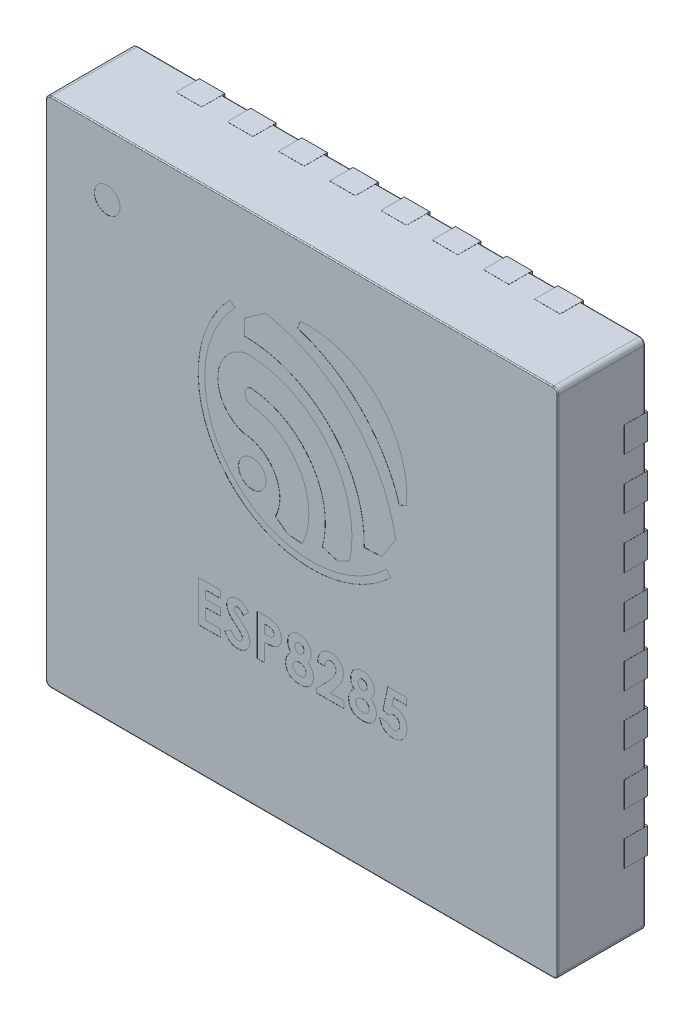
SolidWorks part; units mm, degrees
other "ESP8285-SoC" parameters "D5"=0.3678, "D1"=3.1308, "D2"=3.0402, "D3"=0.4115, "D4"=0.3, "D6"=0.3296, "D7"=0.2637, "D8"=0.9806, "D10"=0.5, "D11"=0.25, "D9"=4
ref_plane "Front Plane" through (0, 0, 0) normal (0, 0, 1) x (1, 0, 0)
ref_plane "Top Plane" through (0, 0, 0) normal (0, 1, 0) x (1, 0, 0)
ref_plane "Right Plane" through (0, 0, 0) normal (1, 0, 0) x (0, 0, -1)
sketch "Sketch1" plane through (0, 0, 0) normal (0, 1, 0) x (1, 0, 0)
  line L1 (-2.5, -2.5) -> (2.5, -2.5)
  line L2 (-2.5, -2.5) -> (-2.5, 2.5)
  line L3 (-2.5, 2.5) -> (2.5, 2.5)
  line L4 (2.5, -2.5) -> (2.5, 2.5)
  line L5 (-2.5, -2.5) -> (2.5, 2.5) construction
  line L6 (-2.5, 2.5) -> (2.5, -2.5) construction
  point P0 (0, 0)
  dimension "D1" = 5
  dimension "D2" = 5
extrude "Boss-Extrude1" add sketch "Sketch1" along normal blind 0.85
fillet "Fillet1" radius 0.05 4 edges at (2.5, 0.425, -2.5) (2.5, 0.425, 2.5) (-2.5, 0.425, 2.5) (-2.5, 0.425, -2.5)
fillet "Fillet2" radius 0.01 16 edges at (2.4854, 0.85, 2.4854) (0, 0.85, 2.5) (-2.4854, 0.85, 2.4854) (-2.5, 0.85, 0) (-2.4854, 0.85, -2.4854) (0, 0.85, -2.5) (2.4854, 0.85, -2.4854) (2.5, 0.85, 0) (2.5, 0, 0) (2.4854, 0, -2.4854) (0, 0, -2.5) (2.4854, 0, 2.4854) (0, 0, 2.5) (-2.4854, 0, 2.4854) (-2.5, 0, 0) (-2.4854, 0, -2.4854)
sketch "Sketch2" plane through (0, 0, 0) normal (0, -1, 0) x (1, 0, 0)
  line L0 (1.55, 1.85) -> (1.85, 1.55)
  line L1 (-1.8, -1.85) -> (1.8, -1.85)
  line L2 (-1.85, -1.8) -> (-1.85, 1.8)
  line L3 (-1.8, 1.85) -> (1.55, 1.85)
  line L4 (1.85, -1.8) -> (1.85, 1.55)
  line L5 (-1.8354, -1.8354) -> (1.85, 1.85) construction
  line L6 (-1.8354, 1.8354) -> (1.8354, -1.8354) construction
  line L7 (1.55, 1.85) -> (1.85, 1.85) construction
  line L8 (1.85, 1.55) -> (1.85, 1.85) construction
  line L9 (-1.85, 1.85) -> (-1.8, 1.85) construction
  line L10 (-1.85, 1.85) -> (-1.8354, 1.8354) construction
  line L11 (-1.85, 1.8) -> (-1.85, 1.85) construction
  line L12 (-1.85, -1.85) -> (-1.85, -1.8) construction
  line L13 (-1.85, -1.85) -> (-1.8354, -1.8354) construction
  line L14 (-1.85, -1.85) -> (-1.8, -1.85) construction
  line L15 (1.85, -1.85) -> (1.85, -1.8) construction
  line L16 (1.8354, -1.8354) -> (1.85, -1.85) construction
  line L17 (1.8, -1.85) -> (1.85, -1.85) construction
  line L18 (0, -1000) -> (0, 49000) construction
  line L23 (-0.375, 2.501) -> (-0.125, 2.501)
  line L24 (-0.375, 2.501) -> (-0.375, 2.101)
  line L25 (-0.375, 2.101) -> (-0.125, 2.101)
  line L26 (-0.125, 2.501) -> (-0.125, 2.101)
  line L27 (-0.375, 2.501) -> (-0.125, 2.101) construction
  line L28 (-0.375, 2.101) -> (-0.125, 2.501) construction
  line L30 (-0.875, 2.501) -> (-0.875, 2.101)
  line L31 (-0.875, 2.501) -> (-0.625, 2.501)
  line L32 (-0.625, 2.501) -> (-0.625, 2.101)
  line L33 (-0.875, 2.101) -> (-0.625, 2.101)
  line L34 (-0.875, 2.101) -> (-0.625, 2.501) construction
  line L35 (-0.875, 2.501) -> (-0.625, 2.101) construction
  line L36 (-1.375, 2.501) -> (-1.375, 2.101)
  line L37 (-1.375, 2.501) -> (-1.125, 2.501)
  line L38 (-1.125, 2.501) -> (-1.125, 2.101)
  line L39 (-1.375, 2.101) -> (-1.125, 2.101)
  line L40 (-1.375, 2.101) -> (-1.125, 2.501) construction
  line L41 (-1.375, 2.501) -> (-1.125, 2.101) construction
  line L42 (-1.875, 2.501) -> (-1.875, 2.101)
  line L43 (-1.875, 2.501) -> (-1.625, 2.501)
  line L44 (-1.625, 2.501) -> (-1.625, 2.101)
  line L45 (-1.875, 2.101) -> (-1.625, 2.101)
  line L46 (-1.875, 2.101) -> (-1.625, 2.501) construction
  line L47 (-1.875, 2.501) -> (-1.625, 2.101) construction
  line L48 (-0.375, 2.501) -> (-0.875, 2.501) construction
  line L162 (-1000, 0) -> (49000, 0) construction
  line L163 (-2.5, 2.5) -> (2.5, 2.5) construction
  line L164 (0.375, 2.501) -> (0.875, 2.501) construction
  line L165 (1.875, 2.501) -> (1.625, 2.101) construction
  line L166 (1.875, 2.101) -> (1.625, 2.501) construction
  line L167 (1.375, 2.501) -> (1.125, 2.101) construction
  line L168 (1.375, 2.101) -> (1.125, 2.501) construction
  line L169 (0.875, 2.501) -> (0.625, 2.101) construction
  line L170 (0.875, 2.101) -> (0.625, 2.501) construction
  line L171 (0.375, 2.101) -> (0.125, 2.501) construction
  line L172 (0.375, 2.501) -> (0.125, 2.101) construction
  line L173 (1.875, 2.101) -> (1.625, 2.101)
  line L174 (1.625, 2.501) -> (1.625, 2.101)
  line L175 (1.875, 2.501) -> (1.625, 2.501)
  line L176 (1.875, 2.501) -> (1.875, 2.101)
  line L177 (1.375, 2.101) -> (1.125, 2.101)
  line L178 (1.125, 2.501) -> (1.125, 2.101)
  line L179 (1.375, 2.501) -> (1.125, 2.501)
  line L180 (1.375, 2.501) -> (1.375, 2.101)
  line L181 (0.875, 2.101) -> (0.625, 2.101)
  line L182 (0.625, 2.501) -> (0.625, 2.101)
  line L183 (0.875, 2.501) -> (0.625, 2.501)
  line L184 (0.875, 2.501) -> (0.875, 2.101)
  line L185 (0.125, 2.501) -> (0.125, 2.101)
  line L186 (0.375, 2.101) -> (0.125, 2.101)
  line L187 (0.375, 2.501) -> (0.375, 2.101)
  line L188 (0.375, 2.501) -> (0.125, 2.501)
  line L189 (0.375, -2.501) -> (0.125, -2.101) construction
  line L190 (0.375, -2.101) -> (0.125, -2.501) construction
  line L191 (0.875, -2.101) -> (0.625, -2.501) construction
  line L192 (0.875, -2.501) -> (0.625, -2.101) construction
  line L193 (1.375, -2.101) -> (1.125, -2.501) construction
  line L194 (1.375, -2.501) -> (1.125, -2.101) construction
  line L195 (1.875, -2.101) -> (1.625, -2.501) construction
  line L196 (1.875, -2.501) -> (1.625, -2.101) construction
  line L197 (0.375, -2.501) -> (0.875, -2.501) construction
  line L198 (-0.375, -2.501) -> (-0.875, -2.501) construction
  line L199 (-1.875, -2.501) -> (-1.625, -2.101) construction
  line L200 (-1.875, -2.101) -> (-1.625, -2.501) construction
  line L201 (-1.375, -2.501) -> (-1.125, -2.101) construction
  line L202 (-1.375, -2.101) -> (-1.125, -2.501) construction
  line L203 (-0.875, -2.501) -> (-0.625, -2.101) construction
  line L204 (-0.875, -2.101) -> (-0.625, -2.501) construction
  line L205 (-0.375, -2.101) -> (-0.125, -2.501) construction
  line L206 (-0.375, -2.501) -> (-0.125, -2.101) construction
  line L207 (0.375, -2.501) -> (0.125, -2.501)
  line L208 (0.375, -2.501) -> (0.375, -2.101)
  line L209 (0.375, -2.101) -> (0.125, -2.101)
  line L210 (0.125, -2.501) -> (0.125, -2.101)
  line L211 (0.875, -2.501) -> (0.875, -2.101)
  line L212 (0.875, -2.501) -> (0.625, -2.501)
  line L213 (0.625, -2.501) -> (0.625, -2.101)
  line L214 (0.875, -2.101) -> (0.625, -2.101)
  line L215 (1.375, -2.501) -> (1.375, -2.101)
  line L216 (1.375, -2.501) -> (1.125, -2.501)
  line L217 (1.125, -2.501) -> (1.125, -2.101)
  line L218 (1.375, -2.101) -> (1.125, -2.101)
  line L219 (1.875, -2.501) -> (1.875, -2.101)
  line L220 (1.875, -2.501) -> (1.625, -2.501)
  line L221 (1.625, -2.501) -> (1.625, -2.101)
  line L222 (1.875, -2.101) -> (1.625, -2.101)
  line L223 (-1.875, -2.101) -> (-1.625, -2.101)
  line L224 (-1.625, -2.501) -> (-1.625, -2.101)
  line L225 (-1.875, -2.501) -> (-1.625, -2.501)
  line L226 (-1.875, -2.501) -> (-1.875, -2.101)
  line L227 (-1.375, -2.101) -> (-1.125, -2.101)
  line L228 (-1.125, -2.501) -> (-1.125, -2.101)
  line L229 (-1.375, -2.501) -> (-1.125, -2.501)
  line L230 (-1.375, -2.501) -> (-1.375, -2.101)
  line L231 (-0.875, -2.101) -> (-0.625, -2.101)
  line L232 (-0.625, -2.501) -> (-0.625, -2.101)
  line L233 (-0.875, -2.501) -> (-0.625, -2.501)
  line L234 (-0.875, -2.501) -> (-0.875, -2.101)
  line L235 (-0.125, -2.501) -> (-0.125, -2.101)
  line L236 (-0.375, -2.101) -> (-0.125, -2.101)
  line L237 (-0.375, -2.501) -> (-0.375, -2.101)
  line L238 (-0.375, -2.501) -> (-0.125, -2.501)
  line L239 (2.501, 0.375) -> (2.101, 0.125) construction
  line L240 (2.101, 0.375) -> (2.501, 0.125) construction
  line L241 (2.101, 0.875) -> (2.501, 0.625) construction
  line L242 (2.501, 0.875) -> (2.101, 0.625) construction
  line L243 (2.101, 1.375) -> (2.501, 1.125) construction
  line L244 (2.501, 1.375) -> (2.101, 1.125) construction
  line L245 (2.101, 1.875) -> (2.501, 1.625) construction
  line L246 (2.501, 1.875) -> (2.101, 1.625) construction
  line L247 (2.501, 0.375) -> (2.501, 0.875) construction
  line L248 (2.501, -0.375) -> (2.501, -0.875) construction
  line L249 (2.501, -1.875) -> (2.101, -1.625) construction
  line L250 (2.101, -1.875) -> (2.501, -1.625) construction
  line L251 (2.501, -1.375) -> (2.101, -1.125) construction
  line L252 (2.101, -1.375) -> (2.501, -1.125) construction
  line L253 (2.501, -0.875) -> (2.101, -0.625) construction
  line L254 (2.101, -0.875) -> (2.501, -0.625) construction
  line L255 (2.101, -0.375) -> (2.501, -0.125) construction
  line L256 (2.501, -0.375) -> (2.101, -0.125) construction
  line L257 (2.501, 0.375) -> (2.501, 0.125)
  line L258 (2.501, 0.375) -> (2.101, 0.375)
  line L259 (2.101, 0.375) -> (2.101, 0.125)
  line L260 (2.501, 0.125) -> (2.101, 0.125)
  line L261 (2.501, 0.875) -> (2.101, 0.875)
  line L262 (2.501, 0.875) -> (2.501, 0.625)
  line L263 (2.501, 0.625) -> (2.101, 0.625)
  line L264 (2.101, 0.875) -> (2.101, 0.625)
  line L265 (2.501, 1.375) -> (2.101, 1.375)
  line L266 (2.501, 1.375) -> (2.501, 1.125)
  line L267 (2.501, 1.125) -> (2.101, 1.125)
  line L268 (2.101, 1.375) -> (2.101, 1.125)
  line L269 (2.501, 1.875) -> (2.101, 1.875)
  line L270 (2.501, 1.875) -> (2.501, 1.625)
  line L271 (2.501, 1.625) -> (2.101, 1.625)
  line L272 (2.101, 1.875) -> (2.101, 1.625)
  line L273 (2.101, -1.875) -> (2.101, -1.625)
  line L274 (2.501, -1.625) -> (2.101, -1.625)
  line L275 (2.501, -1.875) -> (2.501, -1.625)
  line L276 (2.501, -1.875) -> (2.101, -1.875)
  line L277 (2.101, -1.375) -> (2.101, -1.125)
  line L278 (2.501, -1.125) -> (2.101, -1.125)
  line L279 (2.501, -1.375) -> (2.501, -1.125)
  line L280 (2.501, -1.375) -> (2.101, -1.375)
  line L281 (2.101, -0.875) -> (2.101, -0.625)
  line L282 (2.501, -0.625) -> (2.101, -0.625)
  line L283 (2.501, -0.875) -> (2.501, -0.625)
  line L284 (2.501, -0.875) -> (2.101, -0.875)
  line L285 (2.501, -0.125) -> (2.101, -0.125)
  line L286 (2.101, -0.375) -> (2.101, -0.125)
  line L287 (2.501, -0.375) -> (2.101, -0.375)
  line L288 (2.501, -0.375) -> (2.501, -0.125)
  line L289 (-2.501, -0.375) -> (-2.101, -0.125) construction
  line L290 (-2.101, -0.375) -> (-2.501, -0.125) construction
  line L291 (-2.101, -0.875) -> (-2.501, -0.625) construction
  line L292 (-2.501, -0.875) -> (-2.101, -0.625) construction
  line L293 (-2.101, -1.375) -> (-2.501, -1.125) construction
  line L294 (-2.501, -1.375) -> (-2.101, -1.125) construction
  line L295 (-2.101, -1.875) -> (-2.501, -1.625) construction
  line L296 (-2.501, -1.875) -> (-2.101, -1.625) construction
  line L297 (-2.501, -0.375) -> (-2.501, -0.875) construction
  line L298 (-2.501, 0.375) -> (-2.501, 0.875) construction
  line L299 (-2.501, 1.875) -> (-2.101, 1.625) construction
  line L300 (-2.101, 1.875) -> (-2.501, 1.625) construction
  line L301 (-2.501, 1.375) -> (-2.101, 1.125) construction
  line L302 (-2.101, 1.375) -> (-2.501, 1.125) construction
  line L303 (-2.501, 0.875) -> (-2.101, 0.625) construction
  line L304 (-2.101, 0.875) -> (-2.501, 0.625) construction
  line L305 (-2.101, 0.375) -> (-2.501, 0.125) construction
  line L306 (-2.501, 0.375) -> (-2.101, 0.125) construction
  line L307 (-2.501, -0.375) -> (-2.501, -0.125)
  line L308 (-2.501, -0.375) -> (-2.101, -0.375)
  line L309 (-2.101, -0.375) -> (-2.101, -0.125)
  line L310 (-2.501, -0.125) -> (-2.101, -0.125)
  line L311 (-2.501, -0.875) -> (-2.101, -0.875)
  line L312 (-2.501, -0.875) -> (-2.501, -0.625)
  line L313 (-2.501, -0.625) -> (-2.101, -0.625)
  line L314 (-2.101, -0.875) -> (-2.101, -0.625)
  line L315 (-2.501, -1.375) -> (-2.101, -1.375)
  line L316 (-2.501, -1.375) -> (-2.501, -1.125)
  line L317 (-2.501, -1.125) -> (-2.101, -1.125)
  line L318 (-2.101, -1.375) -> (-2.101, -1.125)
  line L319 (-2.501, -1.875) -> (-2.101, -1.875)
  line L320 (-2.501, -1.875) -> (-2.501, -1.625)
  line L321 (-2.501, -1.625) -> (-2.101, -1.625)
  line L322 (-2.101, -1.875) -> (-2.101, -1.625)
  line L323 (-2.101, 1.875) -> (-2.101, 1.625)
  line L324 (-2.501, 1.625) -> (-2.101, 1.625)
  line L325 (-2.501, 1.875) -> (-2.501, 1.625)
  line L326 (-2.501, 1.875) -> (-2.101, 1.875)
  line L327 (-2.101, 1.375) -> (-2.101, 1.125)
  line L328 (-2.501, 1.125) -> (-2.101, 1.125)
  line L329 (-2.501, 1.375) -> (-2.501, 1.125)
  line L330 (-2.501, 1.375) -> (-2.101, 1.375)
  line L331 (-2.101, 0.875) -> (-2.101, 0.625)
  line L332 (-2.501, 0.625) -> (-2.101, 0.625)
  line L333 (-2.501, 0.875) -> (-2.501, 0.625)
  line L334 (-2.501, 0.875) -> (-2.101, 0.875)
  line L335 (-2.501, 0.125) -> (-2.101, 0.125)
  line L336 (-2.101, 0.375) -> (-2.101, 0.125)
  line L337 (-2.501, 0.375) -> (-2.101, 0.375)
  line L338 (-2.501, 0.375) -> (-2.501, 0.125)
  arc A0 (-1.8, 1.85) -> (-1.85, 1.8) centre (-1.8, 1.8) ccw
  arc A1 (-1.85, -1.8) -> (-1.8, -1.85) centre (-1.8, -1.8) ccw
  arc A2 (1.8, -1.85) -> (1.85, -1.8) centre (1.8, -1.8) ccw
  point P0 (0, 0)
  point P12 (-0.25, 2.301)
  point P60 (0.25, 2.301)
  point P93 (0.25, -2.301)
  point P94 (-0.25, -2.301)
  point P127 (2.301, 0.25)
  point P128 (2.301, -0.25)
  point P161 (-2.301, -0.25)
  point P162 (-2.301, 0.25)
  dimension "D5" = 0.1
  dimension "D1" = 3.7
  dimension "D2" = 3.7
  dimension "D4" = 45
  dimension "D6" = 0.4
  dimension "D7" = 0.25
  dimension "D8" = 0.25
  dimension "D11" = 0.001
  dimension "D3" = 0.3
extrude "Boss-Extrude2" add sketch "Sketch2" along normal blind 0.025 and the other way blind 0.203
sketch "Sketch3" plane through (0, 0.85, 0) normal (0, 1, 0) x (1, 0, 0)
  line L7 (-2.5, 1.245) -> (2.5, 1.245) construction
  line L8 (-2.5, 2.5) -> (-2.5, -2.5) construction
  line L9 (2.45, -2.5) -> (-2.45, -2.5) construction
  line L11 (2.5, 2.45) -> (2.5, -2.45) construction
  line L12 (-0.9518, -0.7471) -> (-1.0208, -0.7765)
  line L13 (0.0158, -1.8185) -> (0.0421, -1.7451)
  line L14 (-0.6089, -0.2172) -> (-0.779, -0.2245)
  line L15 (-0.779, -0.2245) -> (-0.9165, -0.4344)
  line L16 (0.3554, -1.7159) -> (0.5618, -1.5711)
  line L17 (0.5618, -1.5711) -> (0.5618, -1.419)
  line L18 (0.6522, -1.6116) -> (0.7003, -1.6542)
  line L19 (-0.8697, -0.0941) -> (-0.8269, -0.142)
  line L20 (0.2577, -0.0472) -> (0.1393, 0.0424)
  line L21 (0.1393, 0.0424) -> (-0.0028, 0.0549)
  line L22 (-0.199, -0.0176) -> (-0.3492, 0.0271)
  line L23 (-0.3492, 0.0271) -> (-0.4663, -0.0315)
  line L24 (0, 0) -> (0, 2.49) construction
  line L25 (2.45, 2.49) -> (-2.45, 2.49) construction
  circle A10 centre (1.9, -1.9) radius 0.125
  arc A11 (-0.9518, -0.7471) -> (0.0421, -1.7451) centre (0.4836, -0.3116) ccw
  arc A12 (-0.9165, -0.4344) -> (0.3554, -1.7159) centre (0.6355, -0.1661) ccw
  arc A13 (0.5445, -1.2833) -> (0.574, -0.5963) centre (0.4641, -0.9357) ccw
  arc A14 (0.7003, -1.6542) -> (-0.8697, -0.0941) centre (-0.0948, -0.8843) ccw
  circle A15 centre (0.4836, -0.295) radius 0.1343
  arc A16 (-0.199, -0.0176) -> (0.5015, -1.0117) centre (0.551, -0.233) ccw
  arc A17 (0.2577, -0.0472) -> (0.574, -0.5963) centre (0.5901, -0.2214) ccw
  arc A18 (-0.0028, 0.0549) -> (0.5041, -0.8706) centre (0.5757, -0.2299) ccw
  arc A19 (-0.4663, -0.0315) -> (0.5445, -1.2833) centre (0.5449, -0.249) ccw
  arc A20 (0.6522, -1.6116) -> (-0.8269, -0.142) centre (-0.0948, -0.8843) ccw
  arc A21 (-0.6089, -0.2172) -> (0.5618, -1.419) centre (0.5606, -0.2491) ccw
  arc A22 (0.5041, -0.8706) -> (0.5015, -1.0117) centre (0.4804, -0.9407) cw
  arc A23 (-1.0208, -0.7765) -> (0.0158, -1.8185) centre (-0.0638, -0.861) ccw
  text T0 "ESP8285" font "Century Gothic" height 0.4
  point P0 (0, 1.245)
  dimension "D2" = 0.25
  dimension "D3" = 0.6
  dimension "D4" = 0.6
extrude "Cut-Extrude1" cut sketch "Sketch3" against normal blind 0.001
move or copy body "Body-Move/Copy1" bodies to move or copy 131 copy no rotation origin (0, 0, 0) rotation axis (0, 0.7071, 0.7071) rotation angle 180
move or copy body "Body-Move/Copy2" bodies to move or copy 132 copy no translate (0, 0, 0.025)
equation "\"D8@Sketch2\"=\"D10@Sketch2\"/2"
equation "\"D4@Sketch3\"=\"D3@Sketch3\""
